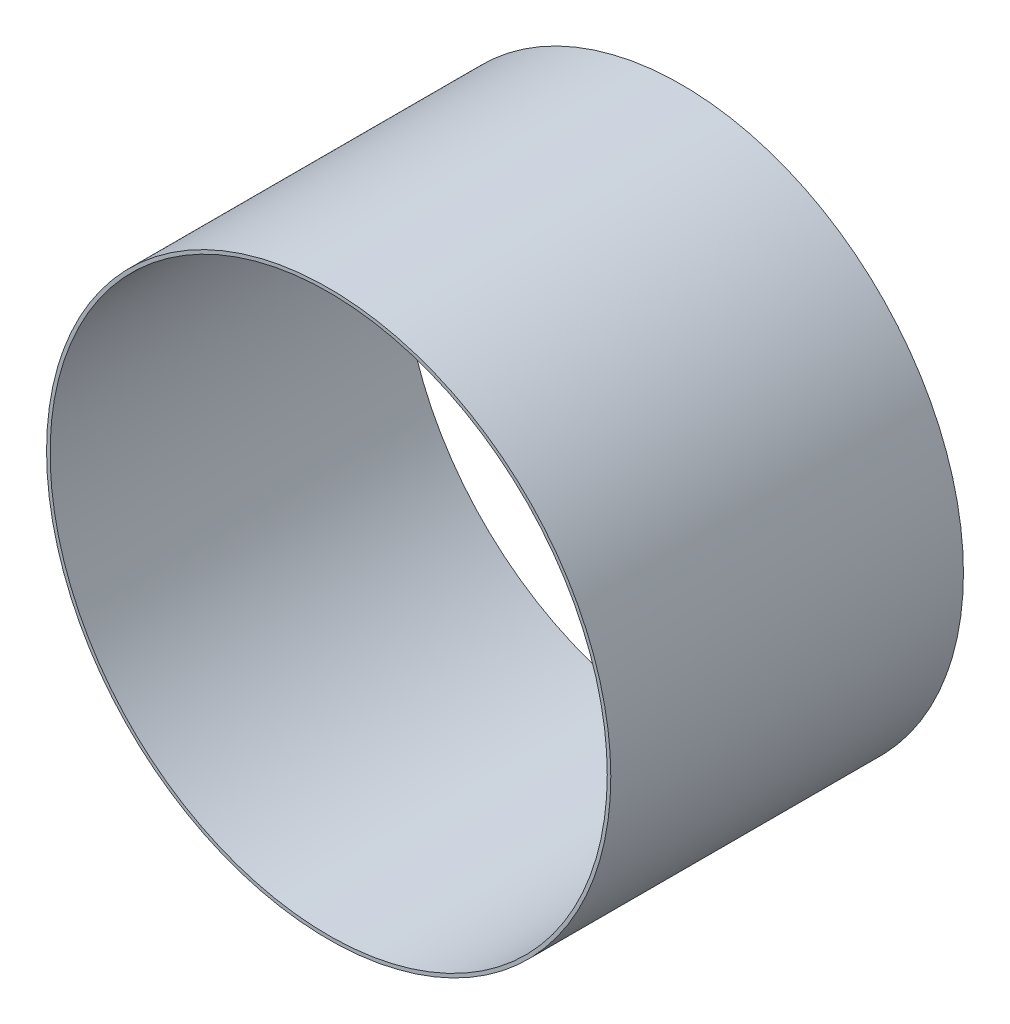
SolidWorks part; units mm, degrees
ref_plane "Alzado" through (0, 0, 0) normal (0, 0, 1) x (1, 0, 0)
ref_plane "Planta" through (0, 0, 0) normal (0, 1, 0) x (1, 0, 0)
ref_plane "Vista lateral" through (0, 0, 0) normal (1, 0, 0) x (0, 0, -1)
sketch "Croquis1" plane through (0, 0, 0) normal (0, 0, 1) x (1, 0, 0)
  circle A0 centre (-81.7044, 22.3952) radius 24
  circle A1 centre (-81.7044, 22.3952) radius 23.7
  dimension "D1" = 48
  dimension "D2" = 47.4
extrude "Saliente-Extruir1" add sketch "Croquis1" along normal blind 30
